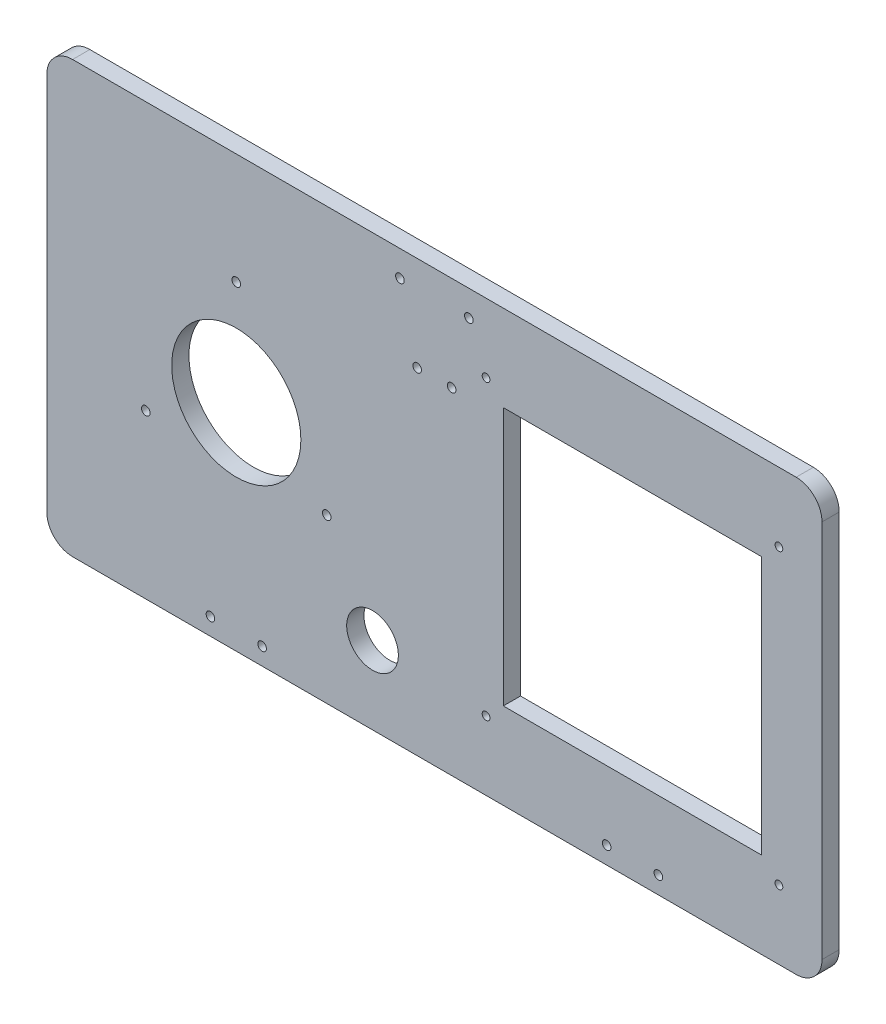
SolidWorks part; units mm, degrees
ref_plane "Alzado" through (0, 0, 0) normal (0, 0, 1) x (1, 0, 0)
ref_plane "Planta" through (0, 0, 0) normal (0, 1, 0) x (1, 0, 0)
ref_plane "Vista lateral" through (0, 0, 0) normal (1, 0, 0) x (0, 0, -1)
sketch "Croquis1" plane through (0, 0, 0) normal (0, 0, 1) x (1, 0, 0)
  line L0 (415, 125) -> (450, 125) construction
  line L1 (15, 0) -> (435, 0)
  line L2 (0, 15) -> (0, 235)
  line L3 (15, 250) -> (435, 250)
  line L4 (450, 15) -> (450, 235)
  line L5 (265, 50) -> (415, 50)
  line L6 (265, 50) -> (265, 200)
  line L7 (265, 200) -> (415, 200)
  line L8 (415, 50) -> (415, 200)
  line L9 (110, 250) -> (110, 0) construction
  line L10 (110, 125) -> (162.5, 94.6891) construction
  line L11 (162.5, 94.6891) -> (110, 185.6218) construction
  line L12 (110, 185.6218) -> (57.5, 94.6891) construction
  line L13 (57.5, 94.6891) -> (162.5, 94.6891) construction
  line L14 (83.75, 140.1554) -> (110, 125) construction
  line L15 (57.5, 94.6891) -> (136.25, 140.1554) construction
  line L16 (225, 250) -> (225, 0) construction
  line L17 (0, 125) -> (450, 125) construction
  line L18 (205, 235) -> (245, 235) construction
  line L23 (215, 195) -> (235, 195) construction
  line L25 (255, 40) -> (255, 210) construction
  line L26 (255, 210) -> (425, 210) construction
  line L27 (425, 40) -> (425, 210) construction
  line L28 (255, 40) -> (425, 40) construction
  line L29 (260, 45) -> (260, 205) construction
  line L30 (260, 205) -> (420, 205) construction
  line L31 (420, 45) -> (420, 205) construction
  line L32 (260, 45) -> (420, 45) construction
  line L33 (340, 200) -> (340, 50) construction
  line L66 (315, 10) -> (325, 10) construction
  line L67 (315, 0) -> (365, 0) construction
  line L68 (315, 0) -> (315, 20) construction
  line L69 (315, 20) -> (365, 20) construction
  line L70 (365, 0) -> (365, 20) construction
  line L71 (355, 10) -> (365, 10) construction
  line L72 (325, 10) -> (355, 10) construction
  line L73 (340, 10) -> (340, 20) construction
  circle A0 centre (110, 125) radius 97.5 construction
  circle A1 centre (110, 185.6218) radius 2.5
  circle A2 centre (162.5, 94.6891) radius 2.5
  circle A3 centre (57.5, 94.6891) radius 2.5
  circle A4 centre (110, 125) radius 37.5
  arc A5 (435, 250) -> (450, 235) centre (435, 235) cw
  arc A6 (435, 0) -> (450, 15) centre (435, 15) ccw
  arc A7 (15, 0) -> (0, 15) centre (15, 15) cw
  arc A8 (0, 235) -> (15, 250) centre (15, 235) cw
  circle A13 centre (205, 235) radius 2.5
  circle A14 centre (245, 235) radius 2.5
  circle A15 centre (189.0965, 45) radius 15
  circle A16 centre (425, 210) radius 2.25
  circle A17 centre (255, 210) radius 2.25
  circle A18 centre (255, 40) radius 2.25
  circle A19 centre (425, 40) radius 2.25
  circle A20 centre (325, 10) radius 2.5
  circle A21 centre (355, 10) radius 2.5
  circle A24 centre (95, 10) radius 2.5
  circle A25 centre (125, 10) radius 2.5
  circle A26 centre (215, 195) radius 2.5
  circle A27 centre (235, 195) radius 2.5
  point P29 (450, 0)
  point P32 (0, 0)
  point P35 (0, 250)
  point P46 (225, 125)
  point P53 (225, 235)
  point P78 (225, 195)
  dimension "D5" = 195
  dimension "D8" = 5
  dimension "D9" = 75
  dimension "D10" = 15
  dimension "D11" = 30
  dimension "D18" = 5
  dimension "D20" = 30
  dimension "D13" = 5
  dimension "D17" = 4.5
  dimension "D1" = 450
  dimension "D2" = 250
  dimension "D3" = 150
  dimension "D4" = 35
  dimension "D6" = 110
  dimension "D7" = 105
  dimension "D12" = 50
  dimension "D14" = 45
  dimension "D15" = 90
  dimension "D16" = 20
  dimension "D19" = 40
  dimension "D21" = 10
  dimension "D23" = 20
  dimension "D24" = 15
  dimension "D27" = 15
  dimension "D22" = 5
extrude "Saliente-Extruir1" add sketch "Croquis1" along normal blind 10
